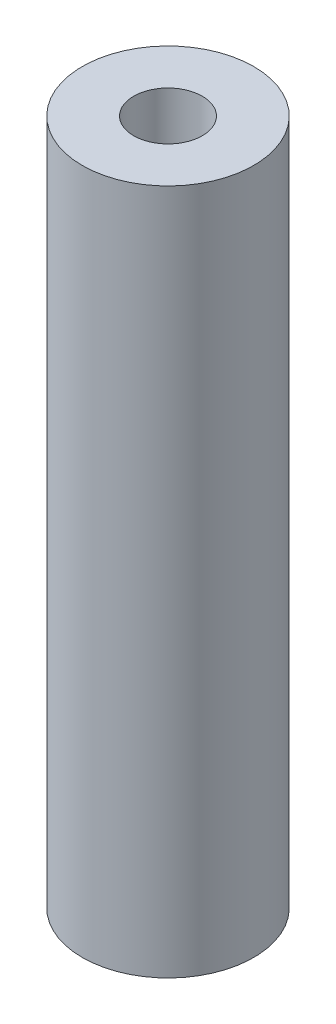
SolidWorks part; units mm, degrees
ref_plane "Спереди" through (0, 0, 0) normal (0, 0, 1) x (1, 0, 0)
ref_plane "Сверху" through (0, 0, 0) normal (0, 1, 0) x (1, 0, 0)
ref_plane "Справа" through (0, 0, 0) normal (1, 0, 0) x (0, 0, -1)
sketch "Эскиз1" plane through (0, 0, 0) normal (0, 1, 0) x (1, 0, 0)
  circle A0 centre (0, 0) radius 1
  circle A1 centre (0, 0) radius 2.5
  dimension "D1" = 5
  dimension "D2" = 2
extrude "Бобышка-Вытянуть1" add sketch "Эскиз1" along normal mid plane 20
equation "\"Ball_bearing_D\"= 12.7"
equation "\"Ball_bearing_h1\"= 9"
equation "\"Ball_bearing_d1\"= 5.9"
equation "\"Ball_bearing_d2\"= 18"
equation "\"Ball_bearing_h2\"= 6.6"
equation "\"Brake_tube_d1\"= 2"
equation "\"Brake_tube_d2\"= 5"
equation "\"Brake_tube_h\"= 20"
equation "\"D1@Эскиз1\"=\"Brake_tube_d2\""
equation "\"D2@Эскиз1\"=\"Brake_tube_d1\""
equation "\"D1@Бобышка-Вытянуть1\"=\"Brake_tube_h\""
